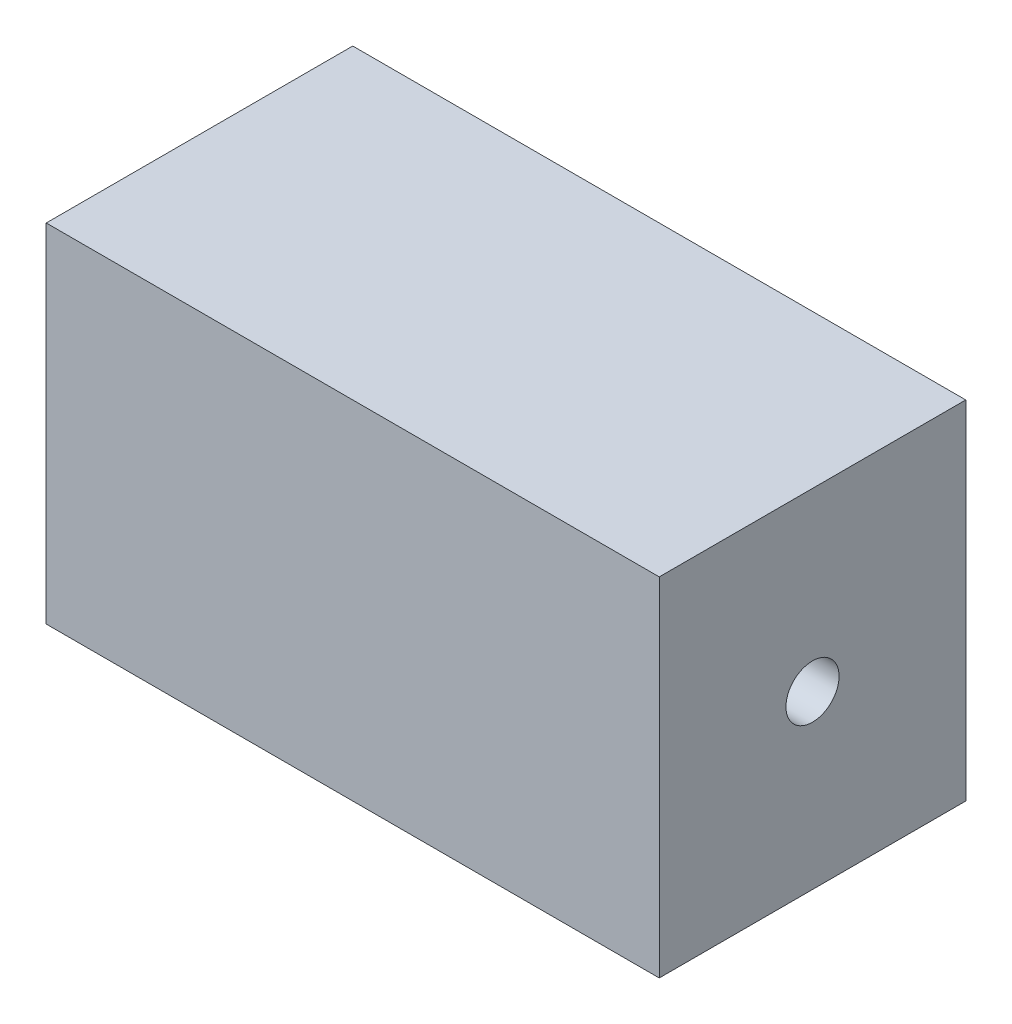
SolidWorks part; units mm, degrees
ref_plane "Front Plane" through (0, 0, 0) normal (0, 0, 1) x (1, 0, 0)
ref_plane "Top Plane" through (0, 0, 0) normal (0, 1, 0) x (1, 0, 0)
ref_plane "Right Plane" through (0, 0, 0) normal (1, 0, 0) x (0, 0, -1)
sketch "Sketch1" plane through (0, 0, 0) normal (0, 1, 0) x (1, 0, 0)
  line L1 (0, 0) -> (190.5, 0)
  line L2 (0, 0) -> (0, 95.25)
  line L3 (0, 95.25) -> (190.5, 95.25)
  line L4 (190.5, 0) -> (190.5, 95.25)
  dimension "D1" = 95.25
  dimension "D2" = 190.5
extrude "Boss-Extrude1" add sketch "Sketch1" along normal blind 107.95 contours L2 L1 L4 L3
sketch "Sketch2" plane through (190.5, 0, 0) normal (1, 0, 0) x (0, 0, -1)
  circle A0 centre (47.625, 53.2869) radius 8.255
  point P2 (0, 0)
  dimension "D1" = 16.51
  dimension "D2" = 47.625
extrude "Cut-Extrude1" cut sketch "Sketch2" against normal mid plane 66.294
